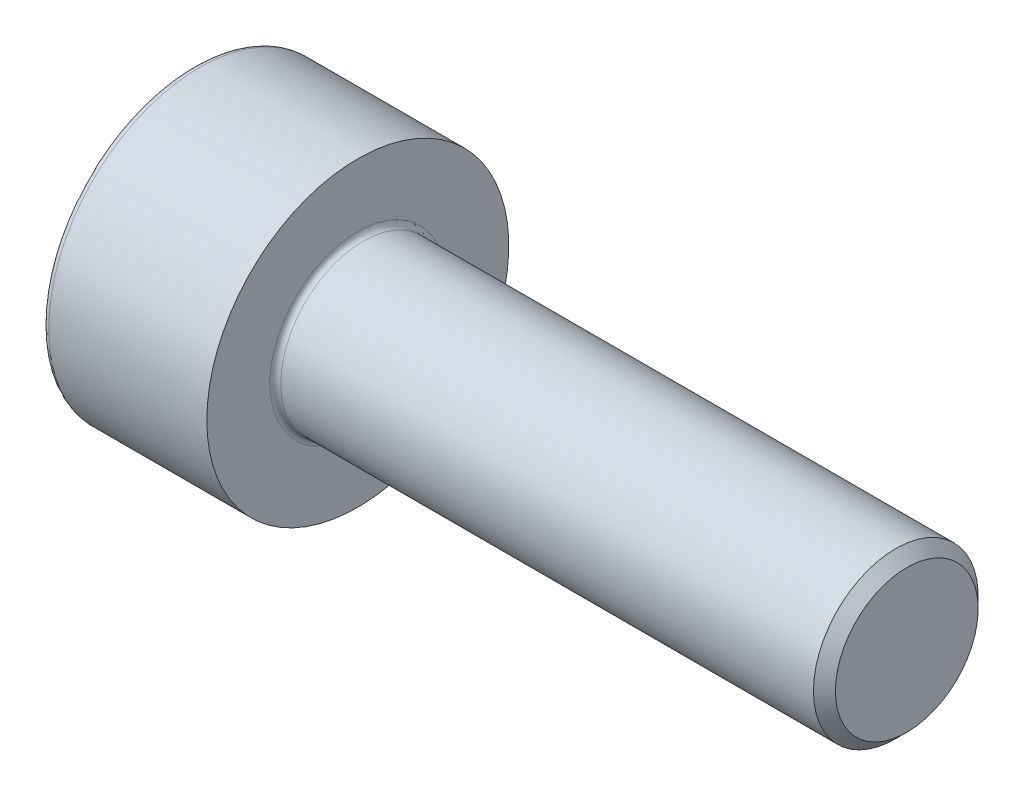
SolidWorks part; units mm, degrees
ref_plane "Front Plane" through (0, 0, 0) normal (0, 0, 1) x (1, 0, 0)
ref_plane "Top Plane" through (0, 0, 0) normal (0, 1, 0) x (1, 0, 0)
ref_plane "Right Plane" through (0, 0, 0) normal (1, 0, 0) x (0, 0, -1)
sketch "Sketch1" plane through (0, 0, 0) normal (0, 0, 1) x (1, 0, 0)
  line L0 (0, 0) -> (0, 2.75)
  line L1 (0, 2.75) -> (3, 2.75)
  line L2 (3, 2.75) -> (3, 0)
  line L3 (0, 0) -> (4.2799, 0) construction
  line L4 (3, 0) -> (13, 0)
  line L5 (13, 0) -> (13, 1.5)
  line L6 (13, 1.5) -> (3, 1.5)
  dimension "D1" = 10
  dimension "D2" = 3
  dimension "D3" = 2.75
  dimension "D4" = 1.5
revolve "Revolve1" add sketch "Sketch1" angle 360 about L3
fillet "Fillet1" radius 0.1 1 edges at (3, 0, 1.5)
fillet "Fillet2" radius 0.12 1 edges at (0, 0, 2.75)
chamfer "Chamfer1" distance 0.2 angle 45 1 edges at (13, 0, 1.5)
sketch "Sketch2" plane through (0, 0, 0) normal (-1, 0, 0) x (0, 0, 1)
  line L1 (0, 1.4434) -> (-1.25, 0.7217)
  line L2 (-1.25, 0.7217) -> (-1.25, -0.7217)
  line L3 (-1.25, -0.7217) -> (0, -1.4434)
  line L4 (0, -1.4434) -> (1.25, -0.7217)
  line L5 (1.25, -0.7217) -> (1.25, 0.7217)
  line L6 (1.25, 0.7217) -> (0, 1.4434)
  circle A0 centre (0, 0) radius 1.25 construction
extrude "Extrude1" cut sketch "Sketch2" against normal blind 1
